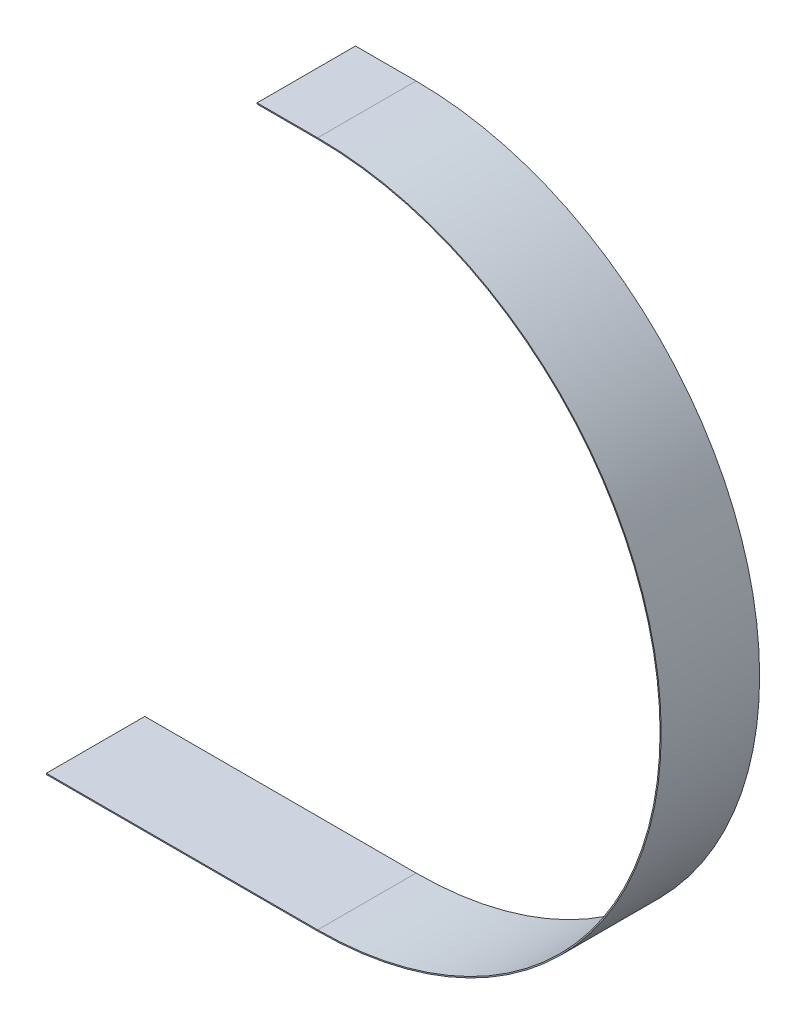
SolidWorks part; units mm, degrees
ref_plane "Front Plane" through (0, 0, 0) normal (0, 0, 1) x (1, 0, 0)
ref_plane "Top Plane" through (0, 0, 0) normal (0, 1, 0) x (1, 0, 0)
ref_plane "Right Plane" through (0, 0, 0) normal (1, 0, 0) x (0, 0, -1)
sketch "Sketch1" plane through (0, 0, 0) normal (0, 0, 1) x (1, 0, 0)
  line L0 (0, 0) -> (28.9418, 0)
  line L1 (28.9418, 73.2968) -> (22.479, 73.2968)
  line L2 (22.479, 73.2968) -> (22.479, 73.1758)
  line L3 (0, 0.121) -> (28.9418, 0.121)
  line L4 (28.9418, 73.1758) -> (22.479, 73.1758)
  line L5 (0, 0.121) -> (0, 0)
  arc A0 (28.9418, 0) -> (28.9418, 73.2968) centre (28.9418, 36.6484) ccw
  arc A1 (28.9418, 0.121) -> (28.9418, 73.1758) centre (28.9418, 36.6484) ccw
  dimension "D1" = 0.121
  dimension "D2" = 6.4627
  dimension "D3" = 28.9418
  dimension "D4" = 73.1758
extrude "Boss-Extrude1" add sketch "Sketch1" along normal mid plane 10.5
